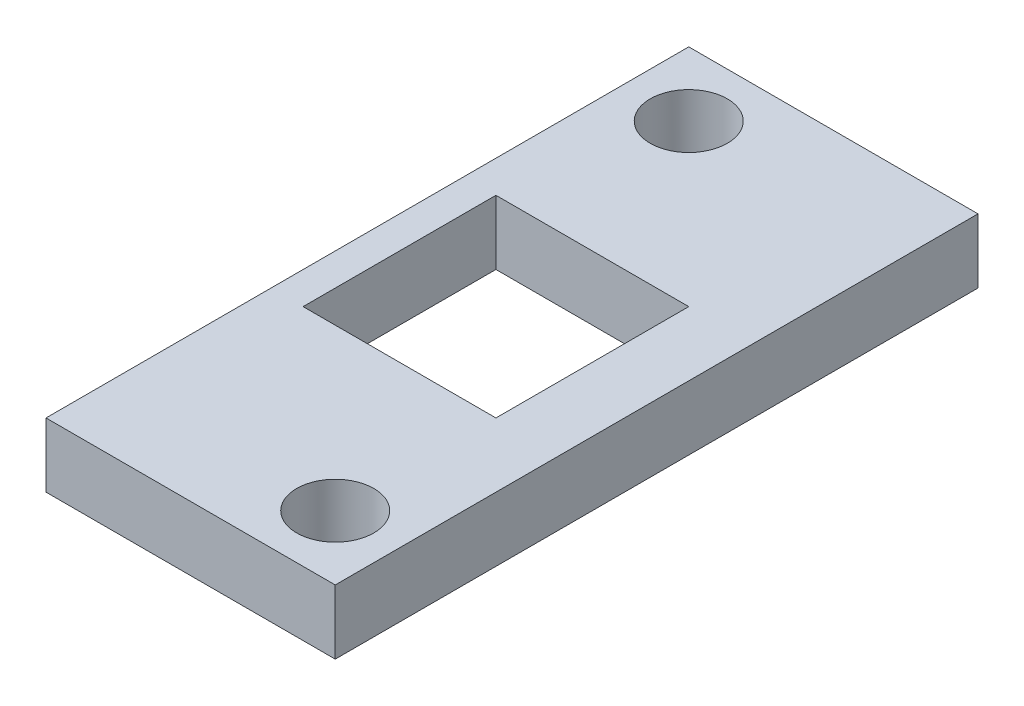
SolidWorks part; units mm, degrees
ref_plane "Спереди" through (0, 0, 0) normal (0, 0, 1) x (1, 0, 0)
ref_plane "Сверху" through (0, 0, 0) normal (0, 1, 0) x (1, 0, 0)
ref_plane "Справа" through (0, 0, 0) normal (1, 0, 0) x (0, 0, -1)
other "Configuration Table"
ref_plane "Плоскость1" through (0, 0, 67) normal (0, 0, 1) x (1, 0, 0)
sketch "Эскиз1" plane through (0, 0, 67) normal (0, 0, 1) x (1, 0, 0)
  line L1 (34, -56) -> (43, -56)
  line L2 (34, -56) -> (34, -54)
  line L3 (34, -54) -> (43, -54)
  line L4 (43, -56) -> (43, -54)
extrude "Carrier_1" add sketch "Эскиз1" along normal blind 20
ref_plane "Плоскость2" through (0, -57, 0) normal (0, 1, 0) x (1, 0, 0)
sketch "Эскиз2" plane through (0, -57, 0) normal (0, 1, 0) x (1, 0, 0)
  line L1 (35, -74) -> (41, -74)
  line L2 (35, -74) -> (35, -80)
  line L3 (35, -80) -> (41, -80)
  line L4 (41, -74) -> (41, -80)
extrude "Tact_6x6_pocket_2" cut sketch "Эскиз2" along normal blind 4
ref_plane "Плоскость3" through (0, -57, 0) normal (0, 1, 0) x (1, 0, 0)
sketch "Эскиз3" plane through (0, -57, 0) normal (0, 1, 0) x (1, 0, 0)
  circle A0 centre (36, -69) radius 1.2
  circle A1 centre (41, -85) radius 1.2
extrude "Carrier_M2_3" cut sketch "Эскиз3" along normal blind 4
